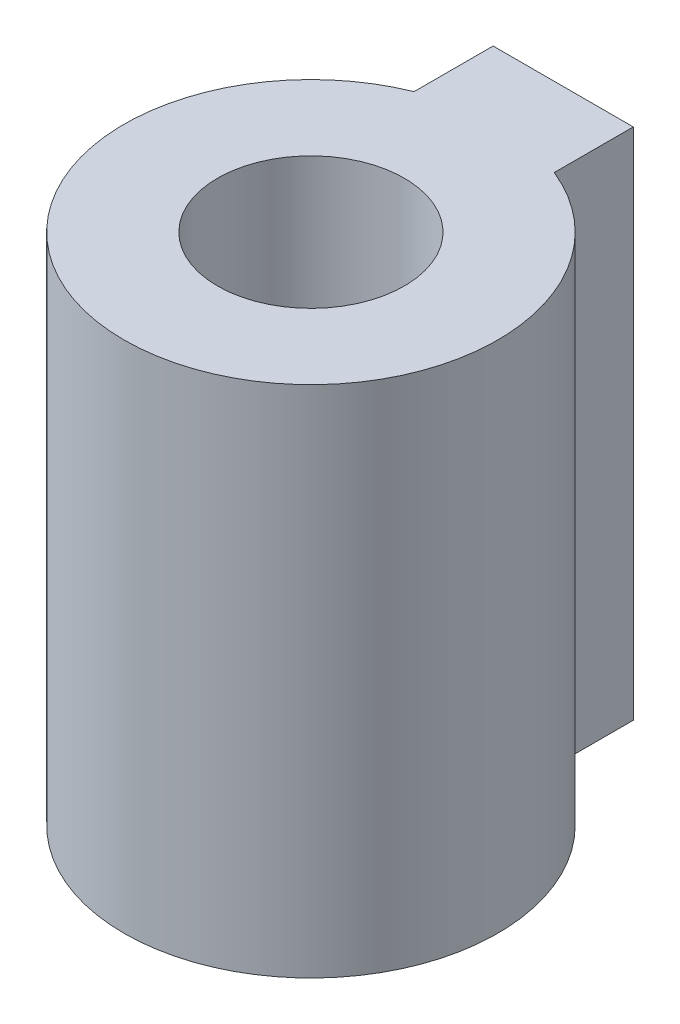
SolidWorks part; units mm, degrees
ref_plane "前视基准面" through (0, 0, 0) normal (0, 0, 1) x (1, 0, 0)
ref_plane "上视基准面" through (0, 0, 0) normal (0, 1, 0) x (1, 0, 0)
ref_plane "右视基准面" through (0, 0, 0) normal (1, 0, 0) x (0, 0, -1)
other "Configuration Table"
sketch "草图4" plane through (0, 0, 0) normal (0, 1, 0) x (1, 0, 0)
  line L1 (-1.5, 0) -> (1.5, 0)
  line L2 (-1.5, 0) -> (-1.5, 5.4)
  line L3 (-1.5, 5.4) -> (1.5, 5.4)
  line L4 (1.5, 0) -> (1.5, 5.4)
  circle A0 centre (0, 0) radius 4
  dimension "D1" = 8
  dimension "D2" = 5.4
  dimension "D3" = 3
extrude "凸台-拉伸3" add sketch "草图4" along normal blind 10 contours L2 A0 L4 L1 | L4 A0 L2 L1 | A0 L4 L3 L2
sketch "草图5" plane through (0, 10, 0) normal (0, 1, 0) x (1, 0, 0)
  line L3 (1.5, 3.7081) -> (1.5, 5.4)
  line L4 (1.5, 5.4) -> (-1.5, 5.4)
  line L5 (-1.5, 5.4) -> (-1.5, 3.7081)
  line L6 (1.5, 3.7081) -> (1.5, 5.4)
  line L7 (1.5, 5.4) -> (-1.5, 5.4)
  line L8 (-1.5, 5.4) -> (-1.5, 3.7081)
  circle A0 centre (0, 0) radius 4
  arc A1 (-1.5, 3.7081) -> (1.5, 3.7081) centre (0, 0) ccw
  arc A2 (-1.5, 3.7081) -> (1.5, 3.7081) centre (0, 0) ccw
  arc M5 (-1.5, 3.7081) -> (1.5, 3.7081) centre (0, 0) ccw
  dimension "D1" = 0
extrude "凸台-拉伸4" add sketch "草图5" along normal blind 1 contours A0 M5
sketch "草图6" plane through (0, 11, 0) normal (0, 1, 0) x (1, 0, 0)
  circle A0 centre (0, 0) radius 2
  circle A1 centre (0, 0) radius 4
  circle A2 centre (0, 0) radius 4
  dimension "D2" = 4
  dimension "D1" = 0
extrude "切除-拉伸1" cut sketch "草图6" against normal blind 3 contours A0
sketch "草图7" plane through (0, 10, 0) normal (0, 1, 0) x (1, 0, 0)
  line L3 (1.5, 3.7081) -> (1.5, 5.4)
  line L4 (1.5, 5.4) -> (-1.5, 5.4)
  line L5 (-1.5, 5.4) -> (-1.5, 3.7081)
  line L6 (1.5, 3.7081) -> (1.5, 5.4)
  line L7 (1.5, 5.4) -> (-1.5, 5.4)
  line L8 (-1.5, 5.4) -> (-1.5, 3.7081)
  arc A1 (1.5, 3.7081) -> (-1.5, 3.7081) centre (0, 0) ccw
  arc A2 (1.5, 3.7081) -> (-1.5, 3.7081) centre (0, 0) ccw
  dimension "D1" = 0
extrude "凸台-拉伸5" add sketch "草图7" along normal blind 1
sketch "草图9" plane through (0, 0, 0) normal (0, -1, 0) x (1, 0, 0)
  line L3 (-1.5, -3.7081) -> (-1.5, -5.4)
  line L4 (-1.5, -5.4) -> (1.5, -5.4)
  line L5 (1.5, -5.4) -> (1.5, -3.7081)
  line L6 (-1.5, -3.7081) -> (-1.5, -5.4)
  line L7 (-1.5, -5.4) -> (1.5, -5.4)
  line L8 (1.5, -5.4) -> (1.5, -3.7081)
  circle A0 centre (0, 0) radius 2
  arc A1 (1.5, -3.7081) -> (-1.5, -3.7081) centre (0, 0) ccw
  arc A2 (1.5, -3.7081) -> (-1.5, -3.7081) centre (0, 0) ccw
  dimension "D2" = 4
  dimension "D1" = 0
extrude "切除-拉伸3" cut sketch "草图9" against normal offset from surface (7 mm away) 1 contours A0 up to face at (0, 8, 2)
sketch "草图10" plane through (0, 7, 0) normal (0, -1, 0) x (1, 0, 0)
  circle A0 centre (0, 0) radius 0.5
  circle A1 centre (0, 0) radius 2
  circle A2 centre (0, 0) radius 2
  dimension "D2" = 1
  dimension "D1" = 0
extrude "切除-拉伸5" cut sketch "草图10" against normal through all contours A0
